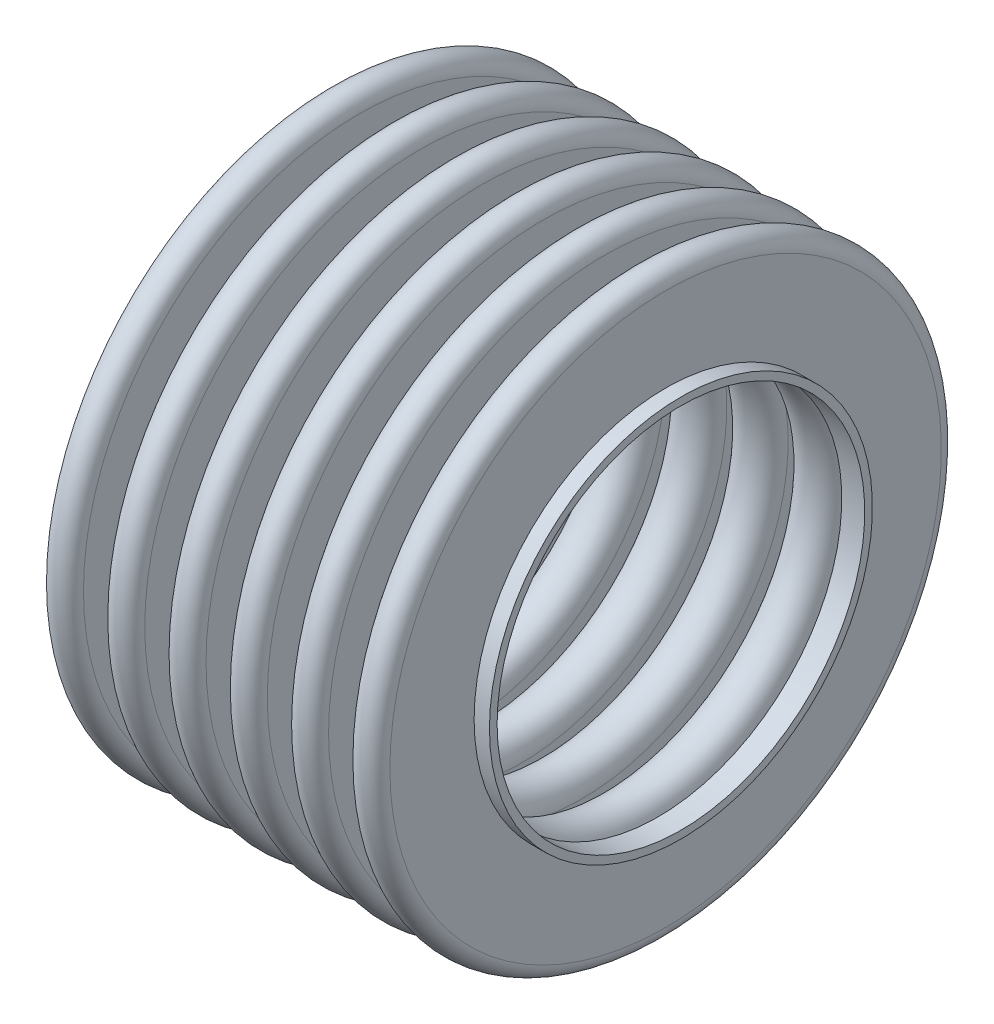
SolidWorks part; units mm, degrees
ref_plane "Front Plane" through (0, 0, 0) normal (0, 0, 1) x (1, 0, 0)
ref_plane "Top Plane" through (0, 0, 0) normal (0, 1, 0) x (1, 0, 0)
ref_plane "Right Plane" through (0, 0, 0) normal (1, 0, 0) x (0, 0, -1)
ref_plane "Plane1" through (0, 0, 0) normal (0, 0, 1) x (1, 0, 0)
sketch "Sketch1" plane through (0, 0, 0) normal (0, 0, 1) x (1, 0, 0)
  line L0 (10, 6.25) -> (10, 6)
  line L1 (10, 6) -> (10.75, 6)
  line L2 (10.75, 6) -> (10.75, 9)
  line L3 (11.25, 9) -> (11.25, 6.75)
  line L4 (12.75, 6.75) -> (12.75, 9)
  line L5 (13.25, 9) -> (13.25, 6.75)
  line L6 (14.75, 6.75) -> (14.75, 9)
  line L7 (15.25, 9) -> (15.25, 6.75)
  line L8 (16.75, 6.75) -> (16.75, 9)
  line L9 (17.25, 9) -> (17.25, 6.75)
  line L10 (18.75, 6.75) -> (18.75, 9)
  line L11 (19.25, 9) -> (19.25, 6.75)
  line L12 (20.75, 6.75) -> (20.75, 9)
  line L13 (21.25, 9) -> (21.25, 6)
  line L14 (21.25, 6) -> (22, 6)
  line L15 (22, 6) -> (22, 6.25)
  line L16 (22, 6.25) -> (21.5, 6.25)
  line L17 (21.5, 6.25) -> (21.5, 9)
  line L18 (20.5, 9) -> (20.5, 6.75)
  line L19 (19.5, 6.75) -> (19.5, 9)
  line L20 (18.5, 9) -> (18.5, 6.75)
  line L21 (17.5, 6.75) -> (17.5, 9)
  line L22 (16.5, 9) -> (16.5, 6.75)
  line L23 (15.5, 6.75) -> (15.5, 9)
  line L24 (14.5, 9) -> (14.5, 6.75)
  line L25 (13.5, 6.75) -> (13.5, 9)
  line L26 (12.5, 9) -> (12.5, 6.75)
  line L27 (11.5, 6.75) -> (11.5, 9)
  line L28 (10.5, 9) -> (10.5, 6.25)
  line L29 (10.5, 6.25) -> (10, 6.25)
  line L30 (22, 0) -> (10, 0) construction
  arc A0 (10.75, 9) -> (11.25, 9) centre (11, 9) cw
  arc A1 (11.25, 6.75) -> (12.75, 6.75) centre (12, 6.75) ccw
  arc A2 (12.75, 9) -> (13.25, 9) centre (13, 9) cw
  arc A3 (13.25, 6.75) -> (14.75, 6.75) centre (14, 6.75) ccw
  arc A4 (14.75, 9) -> (15.25, 9) centre (15, 9) cw
  arc A5 (15.25, 6.75) -> (16.75, 6.75) centre (16, 6.75) ccw
  arc A6 (16.75, 9) -> (17.25, 9) centre (17, 9) cw
  arc A7 (17.25, 6.75) -> (18.75, 6.75) centre (18, 6.75) ccw
  arc A8 (18.75, 9) -> (19.25, 9) centre (19, 9) cw
  arc A9 (19.25, 6.75) -> (20.75, 6.75) centre (20, 6.75) ccw
  arc A10 (20.75, 9) -> (21.25, 9) centre (21, 9) cw
  arc A11 (21.5, 9) -> (20.5, 9) centre (21, 9) ccw
  arc A12 (20.5, 6.75) -> (19.5, 6.75) centre (20, 6.75) cw
  arc A13 (19.5, 9) -> (18.5, 9) centre (19, 9) ccw
  arc A14 (18.5, 6.75) -> (17.5, 6.75) centre (18, 6.75) cw
  arc A15 (17.5, 9) -> (16.5, 9) centre (17, 9) ccw
  arc A16 (16.5, 6.75) -> (15.5, 6.75) centre (16, 6.75) cw
  arc A17 (15.5, 9) -> (14.5, 9) centre (15, 9) ccw
  arc A18 (14.5, 6.75) -> (13.5, 6.75) centre (14, 6.75) cw
  arc A19 (13.5, 9) -> (12.5, 9) centre (13, 9) ccw
  arc A20 (12.5, 6.75) -> (11.5, 6.75) centre (12, 6.75) cw
  arc A21 (11.5, 9) -> (10.5, 9) centre (11, 9) ccw
revolve "Revolve1" add sketch "Sketch1" angle 360 about L30
